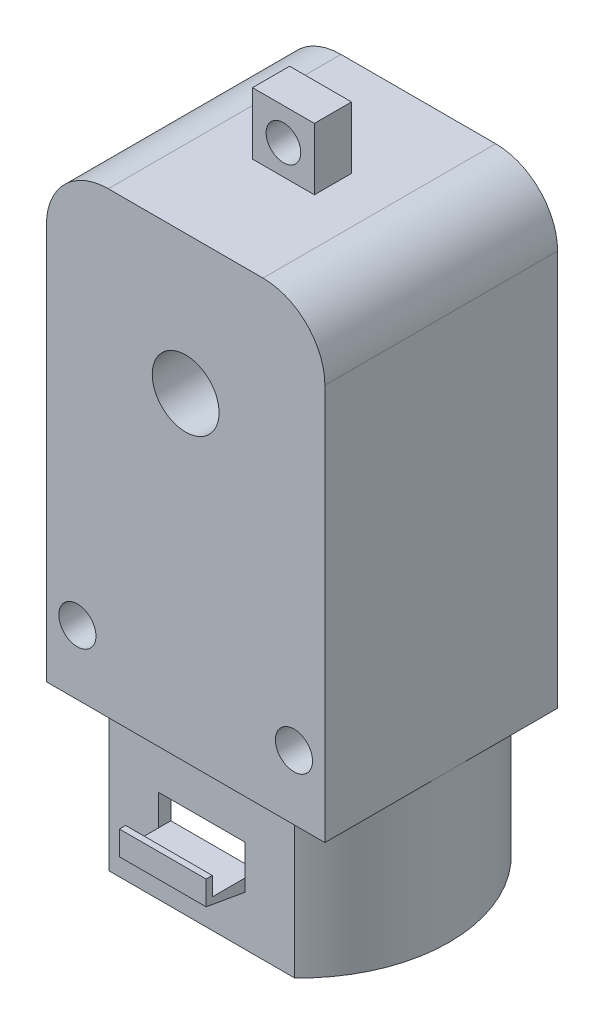
SolidWorks part; units mm, degrees
material "PBT General Purpose"
ref_plane "Alzado" through (0, 0, 0) normal (0, 0, 1) x (1, 0, 0)
ref_plane "Planta" through (0, 0, 0) normal (0, 1, 0) x (1, 0, 0)
ref_plane "Vista lateral" through (0, 0, 0) normal (1, 0, 0) x (0, 0, -1)
sketch "Croquis2" plane through (0, 0, 0) normal (0, 0, 1) x (1, 0, 0)
  line L0 (2.5, -31.8) -> (20, -31.8) construction
  line L1 (5, 0) -> (17.5, 0)
  line L2 (0, -5) -> (0, -37)
  line L3 (0, -37) -> (22.5, -37)
  line L4 (22.5, -5) -> (22.5, -37)
  circle A0 centre (2.5, -31.8) radius 1.5
  circle A1 centre (20, -31.8) radius 1.5
  arc A2 (22.5, -5) -> (17.5, 0) centre (17.5, -5) ccw
  arc A3 (0, -5) -> (5, 0) centre (5, -5) cw
  point P9 (11.25, -37)
  point P10 (11.25, -31.8)
  point P13 (22.5, 0)
  point P16 (0, 0)
  dimension "D3" = 3
  dimension "D4" = 3
  dimension "D7" = 5
  dimension "D1" = 22.5
  dimension "D2" = 37
  dimension "D5" = 17.5
  dimension "D6" = 31.8
extrude "Saliente-Extruir1" add sketch "Croquis2" along normal mid plane 18.8
sketch "Croquis3" plane through (0, 0, 0) normal (0, 0, 1) x (1, 0, 0)
  line L0 (17.5, 0) -> (5, 0) construction
  line L1 (8.75, 0) -> (13.75, 0)
  line L2 (8.75, 0) -> (8.75, 5)
  line L3 (8.75, 5) -> (13.75, 5)
  line L4 (13.75, 0) -> (13.75, 5)
  circle A0 centre (11.25, 2.4) radius 1.4
  point P6 (11.25, 0)
  point P7 (11.25, 5)
  dimension "D3" = 2.8
  dimension "D1" = 5
  dimension "D2" = 5
  dimension "D4" = 2.4
extrude "Saliente-Extruir2" add sketch "Croquis3" along normal mid plane 3
sketch "Croquis5" plane through (0, -37, 0) normal (0, -1, 0) x (1, 0, 0)
  line L0 (18.75, -9.4) -> (3.75, -9.4)
  line L1 (0, -9.4) -> (22.5, -9.4) construction
  line L2 (11.25, -9.4) -> (11.25, 8.1) construction
  line L3 (0, 8.1) -> (11.25, 8.1) construction
  line L4 (0, 9.4) -> (0, -9.4) construction
  line L5 (0, 9.4) -> (22.5, 9.4) construction
  line L6 (3.75, 8.1) -> (18.75, 8.1)
  line L7 (0, 9.4) -> (0, -9.4) construction
  line L8 (4.1601, 7.1) -> (18.3399, 7.1)
  line L9 (18.3399, -8.4) -> (4.1601, -8.4)
  arc A0 (3.75, -9.4) -> (3.75, 8.1) centre (12.0833, -0.65) cw
  arc A1 (18.75, -9.4) -> (18.75, 8.1) centre (10.4167, -0.65) ccw
  arc A2 (4.1601, -8.4) -> (4.1601, 7.1) centre (12.0833, -0.65) cw
  arc A3 (18.3399, -8.4) -> (18.3399, 7.1) centre (10.4167, -0.65) ccw
  point P7 (11.25, 9.4)
  point P18 (11.25, 8.1)
  dimension "D3" = 15
  dimension "D1" = 15
  dimension "D2" = 17.5
  dimension "D4" = 1
extrude "Saliente-Extruir3" add sketch "Croquis5" along normal blind 12
sketch "Croquis6" plane through (0, 0, 8.1) normal (0, 0, 1) x (1, 0, 0)
  line L0 (0, -37) -> (22.5, -37) construction
  line L1 (7.75, -41.5) -> (14.75, -41.5)
  line L2 (7.75, -41.5) -> (7.75, -44)
  line L3 (7.75, -44) -> (14.75, -44)
  line L4 (14.75, -41.5) -> (14.75, -44)
  line L5 (18.75, -49) -> (18.75, -37) construction
  dimension "D1" = 7
  dimension "D2" = 11
  dimension "D3" = 7
  dimension "D4" = 2.5
extrude "Cortar-Extruir1" cut sketch "Croquis6" against normal through all
sketch "Croquis7" plane through (0, 0, 0) normal (1, 0, 0) x (0, 0, -1)
  line L0 (0, 5) -> (0, -49) construction
  line L1 (-1.5, 5) -> (1.5, 5) construction
  line L2 (-8.1, -49) -> (9.4, -49) construction
  line L3 (-8.1, -49) -> (-8.1, -44) construction
  line L4 (-8.1, -49) -> (-8.1, -37) construction
  line L5 (-8.1, -44) -> (-10.75, -44)
  line L6 (-10.75, -44) -> (-10.75, -42.5)
  line L7 (-10.75, -42.5) -> (-11.25, -42.5)
  line L8 (-11.25, -42.5) -> (-11.25, -44.4446)
  line L9 (-11.25, -44.4446) -> (-8.1, -45)
  line L10 (-8.1, -45) -> (-8.1, -44)
  dimension "D1" = 5
  dimension "D2" = 22.5
  dimension "D3" = 0.5
  dimension "D4" = 1.5
  dimension "D5" = 1
  dimension "D6" = 100
extrude "Saliente-Extruir4" add sketch "Croquis7" along normal up to surface (7 mm away) from surface at 7.75 up to face at (14.75, -42.75, 7.6) starting at face at (7.75, -42.75, 7.6)
ref_plane "Plano1" through (0, 0, -0.65) normal (0, 0, -1) x (-1, 0, 0)
mirror "Simetría1" about plane through (0, 0, -0.65) normal (0, 0, -1) of "Saliente-Extruir4"
sketch "Croquis8" plane through (0, 0, -9.4) normal (0, 0, -1) x (-1, 0, 0)
  line L0 (-11.25, 0) -> (-11.25, -11.2) construction
  line L1 (-17.5, 0) -> (-5, 0) construction
  line L2 (-11.25, -11.2) -> (0, -11.2) construction
  line L3 (0, -5) -> (0, -37) construction
  circle A0 centre (-11.25, -11.2) radius 2.7
  dimension "D1" = 2.7
  dimension "D2" = 11.2
extrude "Cortar-Extruir2" cut sketch "Croquis8" against normal through all
